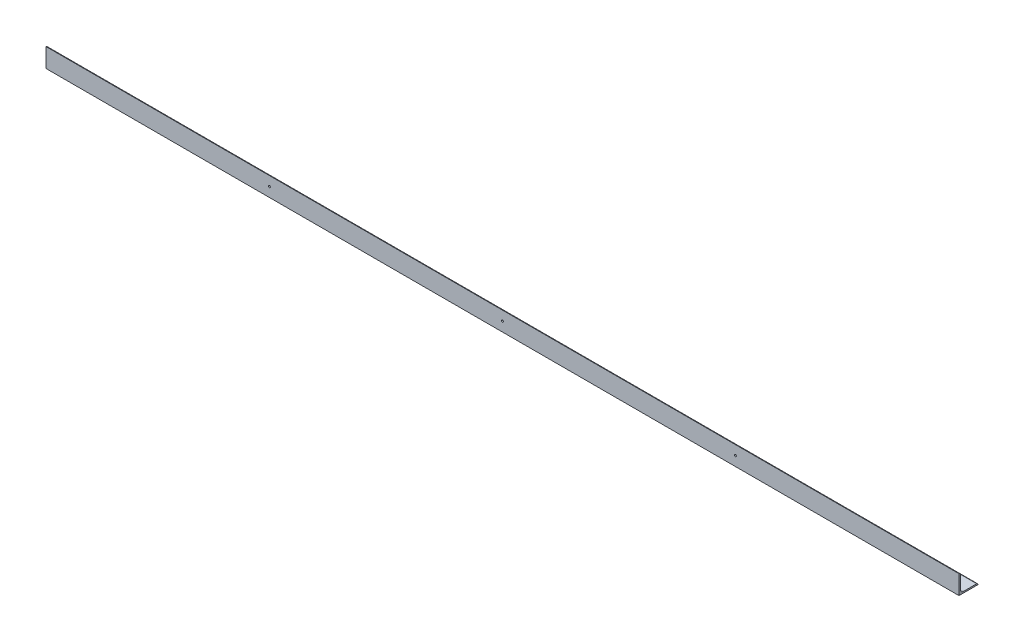
SolidWorks part; units mm, degrees
ref_plane "Front Plane" through (0, 0, 0) normal (0, 0, 1) x (1, 0, 0)
ref_plane "Top Plane" through (0, 0, 0) normal (0, 1, 0) x (1, 0, 0)
ref_plane "Right Plane" through (0, 0, 0) normal (1, 0, 0) x (0, 0, -1)
sketch "Sketch1" plane through (0, 0, 0) normal (0, 1, 0) x (1, 0, 0)
  line L0 (0, 0) -> (1920, 0)
  dimension "D1" = 1920
other "L angle (equal) 40X40X3(2)"
ref_plane "Plane1" through (0, 0, 0) normal (1, 0, 0) x (0, 0, -1)
sketch "Sketch13" plane through (0, 0, 0) normal (1, 0, 0) x (0, 0, -1)
  line L0 (0, 40) -> (0, 0)
  line L2 (3, 37) -> (3, 9)
  line L3 (9, 3) -> (37, 3)
  line L5 (40, 0) -> (0, 0)
  arc A0 (3, 37) -> (0, 40) centre (0, 37) ccw
  arc A1 (40, 0) -> (37, 3) centre (37, 0) ccw
  arc A2 (9, 3) -> (3, 9) centre (9, 9) cw
  point P8 (0, 20)
  point P9 (20, 0)
  point P10 (0, 0)
  dimension "Radius_2" = 3
  dimension "Radius_1" = 6
  dimension "V_leg" = 40
  dimension "H_leg" = 40
  dimension "thickness" = 3
ref_plane "Plane2" through (0, 0, 0) normal (0, -1, 0) x (-1, 0, 0)
sketch "Sketch15" plane through (0, 0, 0) normal (0, -1, 0) x (-1, 0, 0)
  line L0 (-960, 0) -> (-960, 40) construction
  line L4 (0, 0) -> (0, 40)
  line L5 (0, 40) -> (-1920, 40)
  line L6 (-1920, 40) -> (-1920, 0)
  line L7 (-1920, 0) -> (0, 0)
  line L12 (0, 0) -> (0, 40) construction
  line L13 (0, 40) -> (-1920, 40) construction
  line L14 (-1920, 40) -> (-1920, 0) construction
  line L15 (-1920, 0) -> (0, 0) construction
  circle A0 centre (-960, 20) radius 2
  circle A1 centre (-470, 20) radius 2
  circle A2 centre (-1450, 20) radius 2
  dimension "D2" = 2
  dimension "D1" = 0
  dimension "D3" = 2
extrude "Cut-Extrude1" cut sketch "Sketch15" against normal blind 10
ref_plane "Plane3" through (0, 0, 0) normal (0, 0.7071, 0.7071) x (-1, 0, 0)
ref_plane "Plane4" through (0, 0, 0) normal (0, 0, 1) x (1, 0, 0)
sketch "Sketch16" plane through (0, 0, 0) normal (0, 0, 1) x (1, 0, 0)
  line L0 (960, 40) -> (960, 0) construction
  circle A0 centre (960, 20) radius 2
  circle A1 centre (1450, 20) radius 2
  circle A2 centre (470, 20) radius 2
  dimension "D2" = 490
  dimension "D3" = 490
extrude "Cut-Extrude2" cut sketch "Sketch16" against normal blind 3
